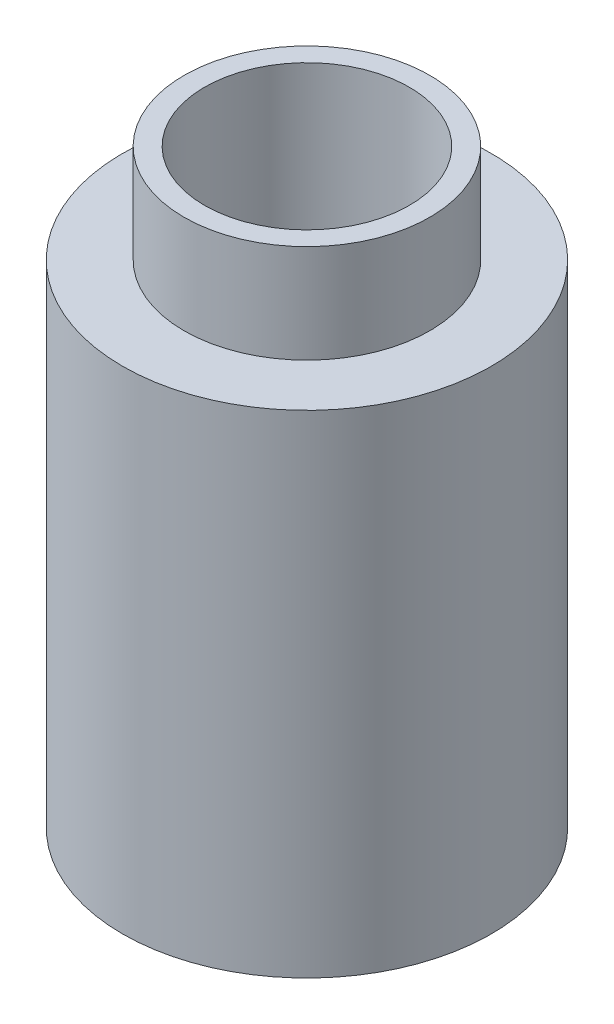
SolidWorks part; units mm, degrees
ref_plane "前视基准面" through (0, 0, 0) normal (0, 0, 1) x (1, 0, 0)
ref_plane "上视基准面" through (0, 0, 0) normal (0, 1, 0) x (1, 0, 0)
ref_plane "右视基准面" through (0, 0, 0) normal (1, 0, 0) x (0, 0, -1)
other "Configuration Table"
sketch "草图1" plane through (0, 0, 0) normal (0, 1, 0) x (1, 0, 0)
  circle A0 centre (0, 0) radius 2.25
  circle A1 centre (0, 0) radius 1.25
  dimension "D1" = 4.5
  dimension "D2" = 2.5
extrude "凸台-拉伸1" add sketch "草图1" along normal blind 6
sketch "草图2" plane through (0, 6, 0) normal (0, 1, 0) x (1, 0, 0)
  circle A0 centre (0, 0) radius 1.25
  circle A1 centre (0, 0) radius 1.5
  dimension "D1" = 3
extrude "凸台-拉伸2" add sketch "草图2" along normal blind 1.2
